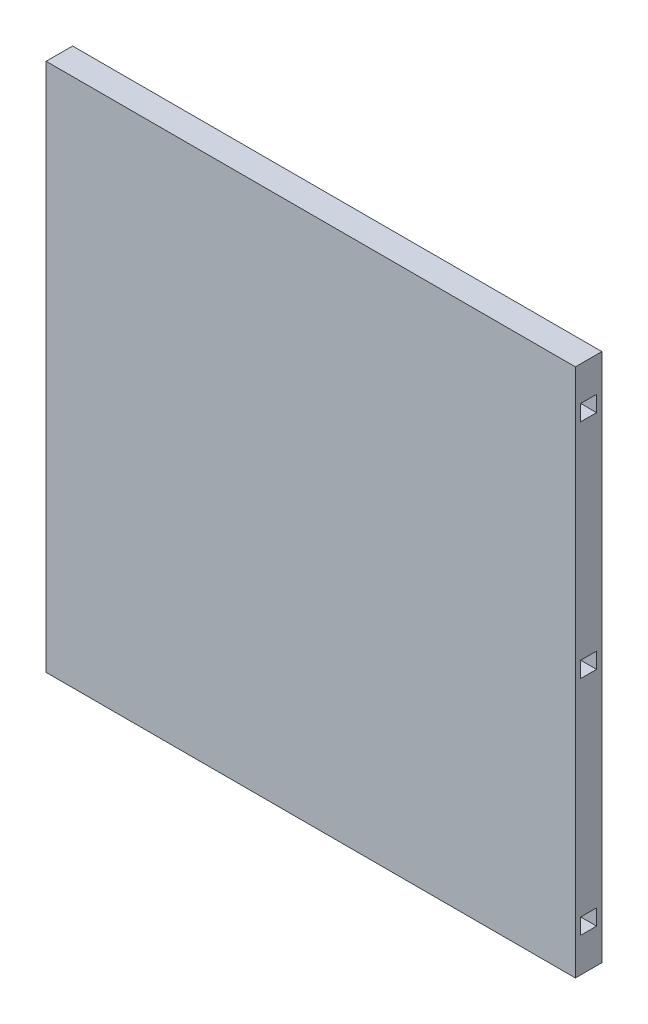
SolidWorks part; units mm, degrees
ref_plane "Front Plane" through (0, 0, 0) normal (0, 0, 1) x (1, 0, 0)
ref_plane "Top Plane" through (0, 0, 0) normal (0, 1, 0) x (1, 0, 0)
ref_plane "Right Plane" through (0, 0, 0) normal (1, 0, 0) x (0, 0, -1)
sketch "Sketch2" plane through (0, 0, 0) normal (0, 0, 1) x (1, 0, 0)
  line L1 (-50, 50) -> (50, 50)
  line L2 (-50, 50) -> (-50, -50)
  line L3 (-50, -50) -> (50, -50)
  line L4 (50, 50) -> (50, -50)
  line L5 (-50, 50) -> (50, -50) construction
  line L6 (-50, -50) -> (50, 50) construction
  point P0 (0, 0)
  dimension "D1" = 100
  dimension "D2" = 100
extrude "Boss-Extrude1" add sketch "Sketch2" along normal blind 5
sketch "Sketch3" plane through (50, 0, 0) normal (1, 0, 0) x (0, 0, -1)
  line L0 (-5, 50) -> (-5, -50)
  line L1 (-5, -50) -> (0, -50)
  line L2 (0, -50) -> (0, 50)
  line L3 (0, 50) -> (-5, 50)
  line L4 (-5, 50) -> (-5, 44.5093)
  line L5 (-5, 44.5093) -> (-5, 39.5093)
  line L6 (-5, 39.5093) -> (0, 39.5093)
  line L7 (0, 39.5093) -> (0, 44.5093)
  line L8 (0, 44.5093) -> (-5, 44.5093)
  line L9 (0, 0) -> (-5, 0)
  line L10 (-5, 0) -> (-5, 2.5)
  line L11 (-5, 2.5) -> (0, 2.5)
  line L12 (0, 2.5) -> (0, -2.5)
  line L13 (0, -2.5) -> (-5, -2.5)
  line L14 (-5, -2.5) -> (-5, 2.5)
  line L15 (0, -44.5093) -> (-5, -44.5093)
  line L16 (0, -39.5093) -> (0, -44.5093)
  line L17 (-5, -39.5093) -> (0, -39.5093)
  line L18 (-5, -44.5093) -> (-5, -39.5093)
  line L19 (0, 44.5093) -> (-1, 44.5093)
  line L20 (0, 44.5093) -> (0, 43.5093)
  line L21 (-2.5, 39.5093) -> (-2.5, 44.5093)
  line L22 (0, 2.5) -> (-1, 2.5)
  line L23 (-4, 40.5093) -> (-1, 40.5093)
  line L24 (-4, 40.5093) -> (-4, 43.5093)
  line L25 (-4, 43.5093) -> (-1, 43.5093)
  line L26 (-1, 40.5093) -> (-1, 43.5093)
  line L27 (-4, 40.5093) -> (-1, 43.5093) construction
  line L28 (-4, 43.5093) -> (-1, 40.5093) construction
  line L29 (0, 2.5) -> (0, 1.5)
  line L30 (-4, -43.5093) -> (-1, -43.5093)
  line L31 (-4, -1.5) -> (-1, -1.5)
  line L32 (-4, -1.5) -> (-4, 1.5)
  line L33 (-4, 1.5) -> (-1, 1.5)
  line L34 (-1, -1.5) -> (-1, 1.5)
  line L35 (-4, -1.5) -> (-1, 1.5) construction
  line L36 (-4, 1.5) -> (-1, -1.5) construction
  line L37 (-1, -40.5093) -> (-1, -43.5093)
  line L38 (-4, -40.5093) -> (-1, -40.5093)
  line L39 (-4, -40.5093) -> (-4, -43.5093)
  point P27 (-2.5, 42.0093)
  point P32 (-2.5, 0)
extrude "Cut-Extrude1" cut sketch "Sketch3" against normal blind 5 contours L23 L26 L25 L21 | L25 L24 L23 L21 | L31 L34 L9 L32 | L9 L34 L33 L32 | L38 L39 L30 L37
sketch "Sketch6" plane through (0, -50, 0) normal (0, -1, 0) x (1, 0, 0)
  line L0 (-50, 0) -> (-50, 5)
  line L1 (-50, 5) -> (-45, 5)
  line L2 (-50, 5) -> (50, 5) construction
  line L3 (-45, 5) -> (-45, 0)
  line L4 (-50, 0) -> (50, 0) construction
  line L5 (-45, 0) -> (-50, 0)
  line L6 (0, 0) -> (0, 2.5)
  line L7 (-47.5, 0) -> (-47.5, 5)
  line L8 (-50, 0) -> (-50, 1)
  line L9 (-50, 0) -> (-49, 0)
  line L10 (46, 1) -> (49, 4) construction
  line L11 (-46, 4) -> (-49, 4)
  line L12 (-46, 4) -> (-46, 1)
  line L13 (-46, 1) -> (-49, 1)
  line L14 (-49, 4) -> (-49, 1)
  line L15 (-46, 4) -> (-49, 1) construction
  line L16 (-46, 1) -> (-49, 4) construction
  line L17 (46, 4) -> (49, 1) construction
  line L18 (49, 4) -> (49, 1)
  line L19 (46, 1) -> (49, 1)
  line L20 (46, 4) -> (46, 1)
  line L21 (46, 4) -> (49, 4)
  line L22 (50, 0) -> (49, 0)
  line L23 (50, 0) -> (50, 1)
  line L24 (47.5, 0) -> (47.5, 5)
  line L25 (45, 0) -> (50, 0)
  line L26 (45, 5) -> (45, 0)
  line L27 (50, 5) -> (45, 5)
  line L28 (50, 0) -> (50, 5)
  line L29 (0, 0) -> (-2.5, 0)
  line L30 (-2.5, 0) -> (2.5, 0)
  line L31 (2.5, 0) -> (2.5, 5)
  line L32 (2.5, 5) -> (-2.5, 5)
  line L33 (-2.5, 5) -> (-2.5, 0)
  line L34 (-2.5, 5) -> (-1.5, 5)
  line L35 (-2.5, 5) -> (-2.5, 4)
  line L37 (1.5, 1) -> (-1.5, 1)
  line L38 (1.5, 1) -> (1.5, 4)
  line L39 (1.5, 4) -> (-1.5, 4)
  line L40 (-1.5, 1) -> (-1.5, 4)
  line L41 (1.5, 1) -> (-1.5, 4) construction
  line L42 (1.5, 4) -> (-1.5, 1) construction
  point P15 (-47.5, 2.5)
  point P34 (47.5, 2.5)
extrude "Cut-Extrude2" cut sketch "Sketch6" against normal blind 5
